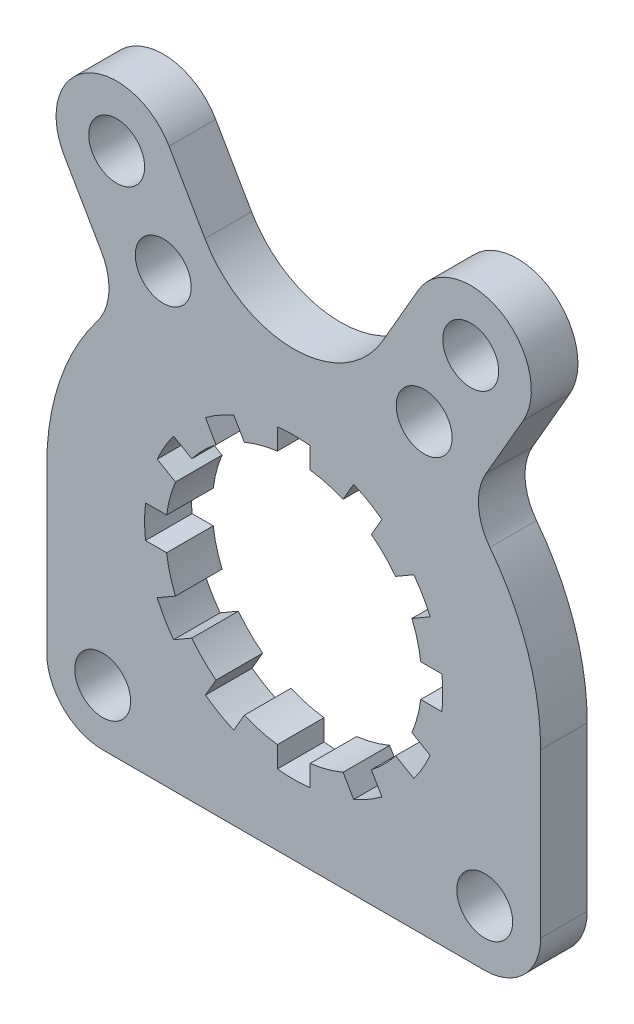
SolidWorks part; units mm, degrees
ref_plane "Alzado" through (0, 0, 0) normal (0, 0, 1) x (1, 0, 0)
ref_plane "Planta" through (0, 0, 0) normal (0, 1, 0) x (1, 0, 0)
ref_plane "Vista lateral" through (0, 0, 0) normal (1, 0, 0) x (0, 0, -1)
sketch "Croquis1" plane through (0, 0, 0) normal (0, 0, 1) x (1, 0, 0)
  line L0 (0, 0) -> (0, 132.8448) construction
  line L1 (0, 0) -> (62.948, 109.0291) construction
  line L2 (12.8729, 29.2966) -> (10.6071, 25.372)
  line L4 (-3.5, 31.808) -> (-3.5, 27.2764)
  line L6 (3.5, 31.808) -> (3.5, 27.2764)
  line L7 (18.9351, 25.7966) -> (16.6693, 21.872)
  line L8 (25.7966, 18.9351) -> (21.872, 16.6693)
  line L9 (29.2966, 12.8729) -> (25.372, 10.6071)
  line L10 (31.808, 3.5) -> (27.2764, 3.5)
  line L11 (31.808, -3.5) -> (27.2764, -3.5)
  line L12 (29.2966, -12.8729) -> (25.372, -10.6071)
  line L13 (25.7966, -18.9351) -> (21.872, -16.6693)
  line L14 (18.9351, -25.7966) -> (16.6693, -21.872)
  line L15 (12.8729, -29.2966) -> (10.6071, -25.372)
  line L16 (3.5, -31.808) -> (3.5, -27.2764)
  line L17 (-3.5, -31.808) -> (-3.5, -27.2764)
  line L18 (-12.8729, -29.2966) -> (-10.6071, -25.372)
  line L19 (-18.9351, -25.7966) -> (-16.6693, -21.872)
  line L20 (-25.7966, -18.9351) -> (-21.872, -16.6693)
  line L21 (-29.2966, -12.8729) -> (-25.372, -10.6071)
  line L22 (-31.808, -3.5) -> (-27.2764, -3.5)
  line L23 (-31.808, 3.5) -> (-27.2764, 3.5)
  line L24 (-29.2966, 12.8729) -> (-25.372, 10.6071)
  line L25 (-25.7966, 18.9351) -> (-21.872, 16.6693)
  line L26 (-18.9351, 25.7966) -> (-16.6693, 21.872)
  line L27 (-12.8729, 29.2966) -> (-10.6071, 25.372)
  line L28 (26.7417, 72.3179) -> (19.0526, 59)
  line L29 (49.2583, 59.3179) -> (41.2583, 45.4615)
  line L30 (53, 0) -> (53, -35)
  line L31 (41, -47) -> (-9.5215, -47)
  line L32 (-41, -47) -> (9.5215, -47)
  line L33 (-53, 0) -> (-53, -35)
  line L34 (-49.2583, 59.3179) -> (-41.2583, 45.4615)
  line L35 (-26.7417, 72.3179) -> (-19.0526, 59)
  circle A0 centre (0, 0) radius 41
  arc A1 (3.5, 31.808) -> (-3.5, 31.808) centre (0, 0) ccw
  arc A2 (-3.5, 27.2764) -> (-10.6071, 25.372) centre (0, 0) ccw
  circle A3 centre (28, 48.4974) radius 6
  circle A4 centre (38, 65.8179) radius 6
  circle A5 centre (41, -35) radius 6
  arc A6 (49.2583, 59.3179) -> (26.7417, 72.3179) centre (38, 65.8179) ccw
  arc A7 (18.9351, 25.7966) -> (12.8729, 29.2966) centre (0, 0) ccw
  arc A8 (29.2966, 12.8729) -> (25.7966, 18.9351) centre (0, 0) ccw
  arc A9 (31.808, -3.5) -> (31.808, 3.5) centre (0, 0) ccw
  arc A10 (25.7966, -18.9351) -> (29.2966, -12.8729) centre (0, 0) ccw
  arc A11 (12.8729, -29.2966) -> (18.9351, -25.7966) centre (0, 0) ccw
  arc A12 (-3.5, -31.808) -> (3.5, -31.808) centre (0, 0) ccw
  arc A13 (-18.9351, -25.7966) -> (-12.8729, -29.2966) centre (0, 0) ccw
  arc A14 (-29.2966, -12.8729) -> (-25.7966, -18.9351) centre (0, 0) ccw
  arc A15 (-31.808, 3.5) -> (-31.808, -3.5) centre (0, 0) ccw
  arc A16 (-25.7966, 18.9351) -> (-29.2966, 12.8729) centre (0, 0) ccw
  arc A17 (-12.8729, 29.2966) -> (-18.9351, 25.7966) centre (0, 0) ccw
  arc A18 (-16.6693, 21.872) -> (-21.872, 16.6693) centre (0, 0) ccw
  arc A19 (-25.372, 10.6071) -> (-27.2764, 3.5) centre (0, 0) ccw
  arc A20 (-27.2764, -3.5) -> (-25.372, -10.6071) centre (0, 0) ccw
  arc A21 (-21.872, -16.6693) -> (-16.6693, -21.872) centre (0, 0) ccw
  arc A22 (-10.6071, -25.372) -> (-3.5, -27.2764) centre (0, 0) ccw
  arc A23 (3.5, -27.2764) -> (10.6071, -25.372) centre (0, 0) ccw
  arc A24 (16.6693, -21.872) -> (21.872, -16.6693) centre (0, 0) ccw
  arc A25 (25.372, -10.6071) -> (27.2764, -3.5) centre (0, 0) ccw
  arc A26 (27.2764, 3.5) -> (25.372, 10.6071) centre (0, 0) ccw
  arc A27 (21.872, 16.6693) -> (16.6693, 21.872) centre (0, 0) ccw
  arc A28 (10.6071, 25.372) -> (3.5, 27.2764) centre (0, 0) ccw
  arc A29 (-19.0526, 59) -> (19.0526, 59) centre (0, 70) ccw
  arc A30 (41.2583, 45.4615) -> (42.1151, 32.1763) centre (51.6506, 39.4615) ccw
  arc A31 (42.1151, 32.1763) -> (53, 0) centre (0, 0) cw
  arc A32 (53, -35) -> (41, -47) centre (41, -35) cw
  circle A33 centre (-41, -35) radius 6
  arc A34 (-53, -35) -> (-41, -47) centre (-41, -35) ccw
  arc A35 (-42.1151, 32.1763) -> (-53, 0) centre (0, 0) ccw
  arc A36 (-41.2583, 45.4615) -> (-42.1151, 32.1763) centre (-51.6506, 39.4615) cw
  circle A37 centre (-28, 48.4974) radius 6
  circle A38 centre (-38, 65.8179) radius 6
  arc A39 (-49.2583, 59.3179) -> (-26.7417, 72.3179) centre (-38, 65.8179) cw
  point P5 (0, 32)
  point P6 (16, 27.7128)
  point P64 (0, 0)
  dimension "D2" = 55
  dimension "D3" = 64
  dimension "D4" = 82
  dimension "D11" = 44
  dimension "D12" = 13
  dimension "D13" = 53
  dimension "D14" = 12
  dimension "D15" = 12
  dimension "D16" = 12
  dimension "D1" = 30
  dimension "D5" = 24
  dimension "D6" = 20
  dimension "D7" = 41
  dimension "D8" = 35
  dimension "D9" = 7
  dimension "D10" = 12
extrude "Saliente-Extruir1" add sketch "Croquis1" along normal blind 10 contours A39 L34 A36 A35 L33 A34 L32 L31 A32 L30 A31 A30 L29 A6 L28 A29 L35 A37 A0 A3 A4 A5 A33 A38 | A0 A28 L2 A7 L7 A27 L8 A8 L9 A26 L10 A9 L11 A25 L12 A10 L13 A24 L14 A11 L15 A23 L16 A12 L17 A22 L18 A13 L19 A21 L20 A14 L21 A20 L22 A15 L23 A19 L24 A16 L25 A18 L26 A17 L27 A2 L4 A1 L6
